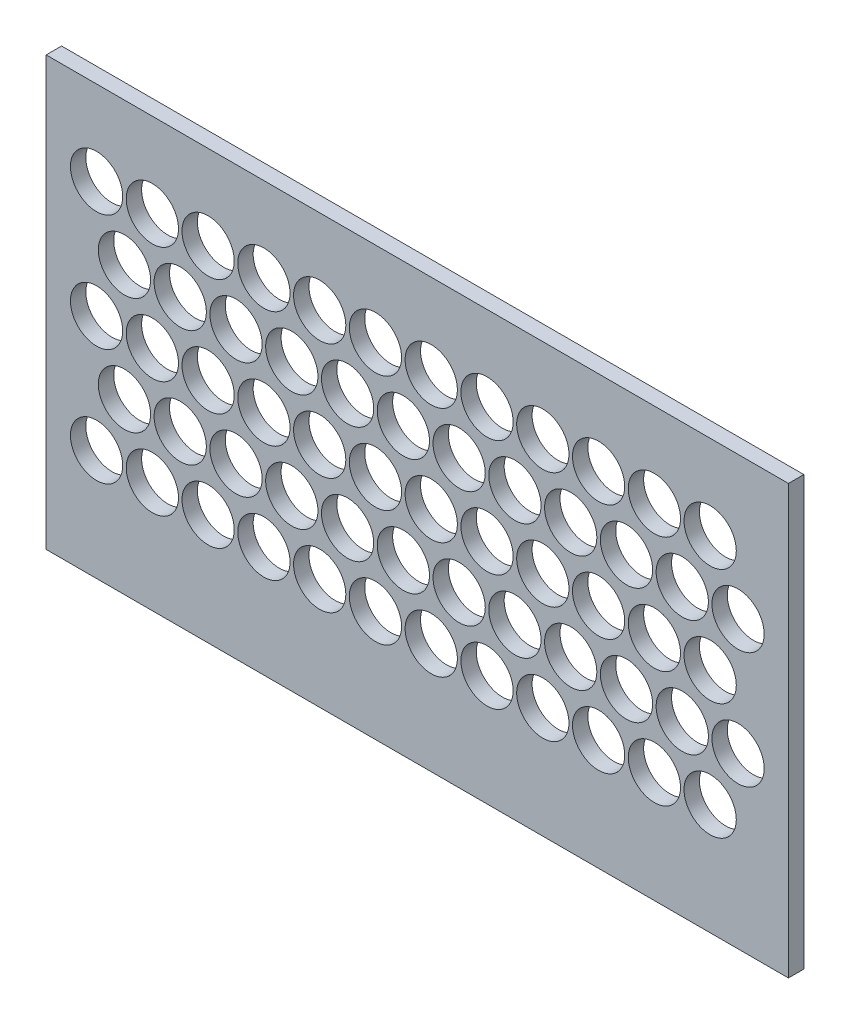
SolidWorks part; units mm, degrees
material "ABS"
ref_plane "X-Y Datum" through (0, 0, 0) normal (0, 0, 1) x (1, 0, 0)
ref_plane "X-Z Datum" through (0, 0, 0) normal (0, 1, 0) x (1, 0, 0)
ref_plane "Y-Z Datum" through (0, 0, 0) normal (1, 0, 0) x (0, 0, -1)
sketch "Sketch1" plane through (0, 0, 0) normal (0, 0, 1) x (1, 0, 0)
  line L1 (-143.025, 58.775) -> (143.025, 58.775)
  line L2 (-143.025, 58.775) -> (-143.025, -58.775)
  line L3 (-143.025, -58.775) -> (143.025, -58.775)
  line L4 (143.025, 58.775) -> (143.025, -58.775)
  line L5 (-143.025, 58.775) -> (143.025, -58.775) construction
  line L6 (-143.025, -58.775) -> (143.025, 58.775) construction
  line L13 (-153.025, -93.775) -> (153.025, -93.775)
  line L14 (-153.025, 79.65) -> (153.025, 79.65)
  line L15 (-153.025, 79.65) -> (-153.025, -93.775)
  line L16 (153.025, 79.65) -> (153.025, -93.775)
  line L17 (153.025, 58.775) -> (153.025, -58.775) construction
  line L18 (-143.025, 79.65) -> (143.025, 79.65) construction
  line L19 (-143.025, -93.775) -> (143.025, -93.775) construction
  line L20 (-153.025, 58.775) -> (-153.025, -58.775) construction
  line L21 (-132.25, -48) -> (-109.25, -48) construction
  circle A0 centre (-132.25, -48) radius 10.775
  circle A1 centre (-109.25, -48) radius 10.775 construction
  circle A2 centre (-120.75, -24) radius 10.775
  point P0 (0, 0)
  point P16 (-120.75, -48)
  dimension "D1" = 21.55
  dimension "D2" = 23
  dimension "D3" = 24
  dimension "D5" = 117.55
  dimension "D6" = 286.05
  dimension "D7" = 35
  dimension "D8" = 20.875
  dimension "D9" = 10
  dimension "D10" = 10
extrude "Boss-Extrude1" add sketch "Sketch1" along normal blind 6.35
sketch "Sketch3" plane through (0, 0, 6.35) normal (0, 0, 1) x (1, 0, 0)
  line L4 (143.025, 58.775) -> (-143.025, 58.775)
  line L5 (143.025, -58.775) -> (143.025, 58.775)
  line L6 (-143.025, -58.775) -> (143.025, -58.775)
  line L7 (-143.025, 58.775) -> (-143.025, -58.775)
  line L8 (143.025, 58.775) -> (-143.025, 58.775)
  line L9 (143.025, -58.775) -> (143.025, 58.775)
  line L10 (-143.025, -58.775) -> (143.025, -58.775)
  line L11 (-143.025, 58.775) -> (-143.025, -58.775)
  circle A1 centre (-120.75, -24) radius 10.775
  circle A2 centre (-120.75, -24) radius 10.775
  circle A3 centre (-132.25, -48) radius 10.775
  circle A4 centre (-132.25, -48) radius 10.775
  dimension "D1" = 0
  dimension "D2" = 0
  dimension "D3" = 0
extrude "Cut-Extrude1" cut sketch "Sketch3" against normal through all contours A4
sketch "Sketch4" plane through (0, 0, 6.35) normal (0, 0, 1) x (1, 0, 0)
  line L4 (143.025, 58.775) -> (-143.025, 58.775)
  line L5 (143.025, -58.775) -> (143.025, 58.775)
  line L6 (-143.025, -58.775) -> (143.025, -58.775)
  line L7 (-143.025, 58.775) -> (-143.025, -58.775)
  line L8 (143.025, 58.775) -> (-143.025, 58.775)
  line L9 (143.025, -58.775) -> (143.025, 58.775)
  line L10 (-143.025, -58.775) -> (143.025, -58.775)
  line L11 (-143.025, 58.775) -> (-143.025, -58.775)
  circle A1 centre (-120.75, -24) radius 10.775
  circle A2 centre (-120.75, -24) radius 10.775
  circle A3 centre (-132.25, -48) radius 10.775
  circle A4 centre (-132.25, -48) radius 10.775
  dimension "D1" = 0
  dimension "D2" = 0
  dimension "D3" = 0
extrude "Cut-Extrude2" cut sketch "Sketch4" against normal through all contours A2
pattern_linear "LPattern1" count 12 spacing 23 along (1, 0, 0) of "Cut-Extrude1"
pattern_linear "LPattern3" count 12 spacing 23 along (1, 0, 0) of "Cut-Extrude2"
pattern_linear "LPattern2" count 3 spacing 48 along (0, 1, 0) of "LPattern1", "Cut-Extrude1"
pattern_linear "LPattern4" count 2 spacing 48 along (0, 1, 0) of "LPattern3", "Cut-Extrude2"
sketch "Sketch13" plane through (0, 79.65, 0) normal (0, 1, 0) x (1, 0, 0)
  line L4 (153.025, 0) -> (-153.025, 0)
  line L5 (-153.025, 0) -> (-153.025, -6.35)
  line L6 (-153.025, -6.35) -> (153.025, -6.35)
  line L9 (-153.025, 0) -> (-153.025, -6.35)
  line L10 (-153.025, -6.35) -> (153.025, -6.35)
  line L12 (153.025, 0) -> (-153.025, 0)
  line L14 (153.025, -6.35) -> (153.025, 0)
  line L15 (153.025, -6.35) -> (153.025, 0)
  dimension "D1" = 0
extrude "Boss-Extrude2" add sketch "Sketch13" along normal blind 3.175
